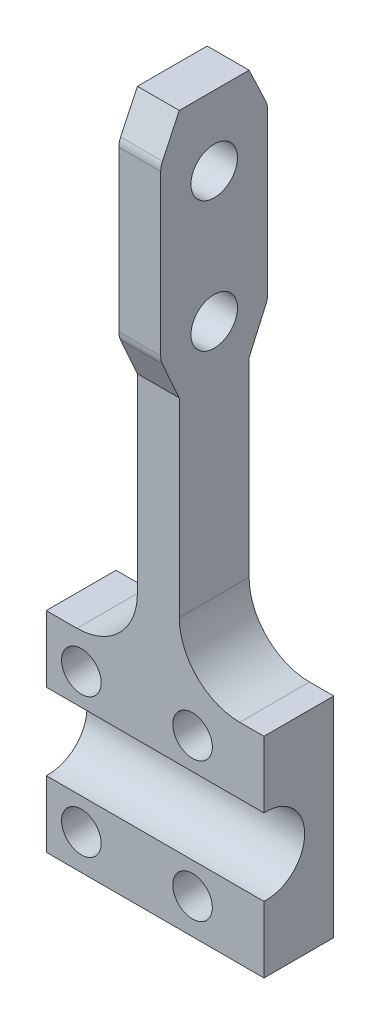
SolidWorks part; units mm, degrees
ref_plane "Front Plane" through (0, 0, 0) normal (0, 0, 1) x (1, 0, 0)
ref_plane "Top Plane" through (0, 0, 0) normal (0, 1, 0) x (1, 0, 0)
ref_plane "Right Plane" through (0, 0, 0) normal (1, 0, 0) x (0, 0, -1)
sketch "Sketch1" plane through (0, 0, 0) normal (0, 0, 1) x (1, 0, 0)
  line L0 (-26.3, 129.9) -> (39.7021, 129.9) construction
  line L1 (-8.1, 22.5) -> (-8.1, 129.9)
  line L3 (0.9, 35.5) -> (0.9, 129.9)
  line L5 (-8.1, 129.9) -> (0.9, 129.9)
  line L12 (-26.3, 22.5) -> (-26.3, -22.5)
  line L13 (-26.3, -22.5) -> (20.5, -22.5)
  line L14 (20.5, -22.5) -> (20.5, 22.5)
  line L15 (20.5, 22.5) -> (13.9, 22.5)
  line L17 (-8.1, 22.5) -> (-26.3, 22.5)
  circle A4 centre (-10.95, -14.95) radius 4.25
  circle A5 centre (12.95, -14.95) radius 4.25
  circle A6 centre (12.95, 14.95) radius 4.25
  circle A7 centre (-10.95, 14.95) radius 4.25
  arc A8 (0.9, 35.5) -> (13.9, 22.5) centre (13.9, 35.5) ccw
  point P32 (-8.1, 22.5)
  dimension "D4" = 13
  dimension "D3" = 9
extrude "Boss-Extrude1" add sketch "Sketch1" along normal blind 15
sketch "Sketch3" plane through (-26.3, 0, 0) normal (-1, 0, 0) x (0, 0, 1)
  line L0 (15, 0) -> (-12.6668, 0) construction
  line L1 (15, 22.5) -> (15, -22.5) construction
  circle A0 centre (14.5, 0) radius 8.25
  dimension "D2" = 16.5
  dimension "D1" = 0.5
extrude "Cut-Extrude1" cut sketch "Sketch3" against normal blind 55.05
sketch "Sketch4" plane through (0.9, 0, 0) normal (1, 0, 0) x (0, 0, -1)
  line L0 (-7.5, 22.5) -> (-7.5, 86.9) construction
  line L1 (-15, 22.5) -> (0, 22.5) construction
  circle A0 centre (-7.5, 86.9) radius 5
  circle A1 centre (-7.5, 114.9) radius 5
  dimension "D1" = 10
  dimension "D2" = 28
extrude "Cut-Extrude3" cut sketch "Sketch4" against normal blind 46.05
sketch "Sketch6" plane through (-8.1, 0, 0) normal (-1, 0, 0) x (0, 0, 1)
  line L0 (15, 76.3869) -> (18.6516, 84.5541)
  line L1 (15, 129.9) -> (15, 22.5) construction
  line L2 (19, 86.1868) -> (19, 120.55)
  line L3 (18.6155, 122.2613) -> (15, 129.9)
  line L4 (7.5, 114.9) -> (7.5, 65.4139) construction
  line L5 (-3.6155, 122.2613) -> (0, 129.9)
  line L6 (-4, 86.1868) -> (-4, 120.55)
  line L7 (0, 76.3869) -> (-3.6516, 84.5541)
  line L8 (0, 76.3869) -> (0, 129.9)
  line L9 (15, 76.3869) -> (15, 129.9)
  arc A0 (19, 120.55) -> (18.6155, 122.2613) centre (15, 120.55) ccw
  arc A1 (18.6516, 84.5541) -> (19, 86.1868) centre (15, 86.1868) ccw
  arc A2 (-3.6516, 84.5541) -> (-4, 86.1868) centre (0, 86.1868) cw
  arc A3 (-4, 120.55) -> (-3.6155, 122.2613) centre (0, 120.55) cw
  dimension "D1" = 4
  dimension "D2" = 4
extrude "Boss-Extrude2" add sketch "Sketch6" against normal up to surface (9 mm away) up to face at (0.9, 86.9, 2.5)
fillet "Fillet1" radius 13 1 edges at (-8.1, 22.5, 7.5)
mirror "Mirror2" about plane through (20.5, -22.5, 15) normal (-1, 0, 0) of bodies 105
delete or keep bodies "Body-Delete/Keep 1" type keep bodies bodies 107
